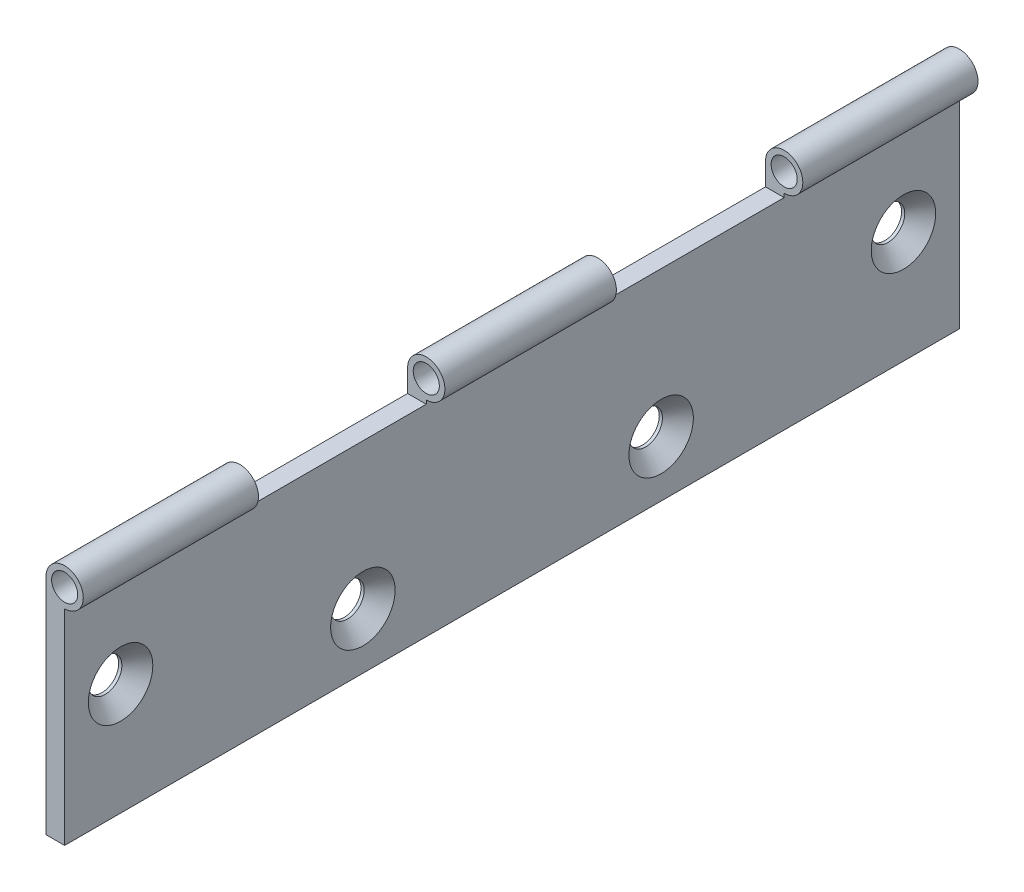
SolidWorks part; units mm, degrees
ref_plane "Front Plane" through (0, 0, 0) normal (0, 0, 1) x (1, 0, 0)
ref_plane "Top Plane" through (0, 0, 0) normal (0, 1, 0) x (1, 0, 0)
ref_plane "Right Plane" through (0, 0, 0) normal (1, 0, 0) x (0, 0, -1)
sketch "Эскиз1" plane through (0, 0, 0) normal (0, 0, 1) x (1, 0, 0)
  line L0 (0, 0) -> (0, 60)
  dimension "D1" = 60
extrude "Вытянуть-Тонкостенный1" add sketch "Эскиз1" along normal mid plane 240 thin
sketch "Эскиз2" plane through (0, 0, 120) normal (0, 0, 1) x (1, 0, 0)
  circle A0 centre (5, 60) radius 5
sweep "По траектории1" add profiles "Эскиз2" path edge at (5, 60, 0)
sketch "Эскиз4" plane through (0, 0, 120) normal (0, 0, 1) x (1, 0, 0)
  circle A0 centre (5, 60) radius 3.5
  arc A1 (5, 55) -> (0, 60) centre (5, 60) ccw construction
extrude "Вырез-Вытянуть1" cut sketch "Эскиз4" against normal through all
hole_wizard "Зенковка для  винта с плоской головкой M81" positions "Эскиз6" profile "Эскиз5" countersink size "M8" standard "Ansi Metric" end condition through all
sketch "Эскиз6" plane through (5, 0, 0) normal (1, 0, 0) x (0, 0, -1)
  point P0 (-105, 30)
  point P2 (-40, 15)
  dimension "D1" = 30
  dimension "D2" = 15
  dimension "D3" = 15
  dimension "D4" = 80
sketch "Эскиз5" plane through (5, 30, 105) normal (0, 1, 0) x (0, 0, -1)
  line L0 (0, 0) -> (0, 5)
  line L1 (0, 5) -> (4.5, 5)
  line L2 (4.5, 5) -> (4.5, 4.15)
  line L3 (4.5, 4.15) -> (8.65, 0)
  line L5 (8.65, 0) -> (0, 0)
  line L6 (-4.5, 4.15) -> (-8.65, 0) construction
  line L11 (0, -6.35) -> (0, 107.95) construction
  dimension "Диаметр сквозного отверстия" = 9
  dimension "Глубина сквозного отверстия" = 5
  dimension "Диаметр передней зенковки" = 17.3
  dimension "Угол передней зенковки" = 90
mirror "Зеркальное отражение1" about plane through (0, 0, 0) normal (0, 0, 1) of "Зенковка для  винта с плоской головкой M81"
sketch "компоновка для вырезов" plane through (5, 0, 0) normal (1, 0, 0) x (0, 0, -1)
  line L5 (-120, 65) -> (-120, 55) construction
  line L6 (120, 54) -> (-120, 54)
  line L7 (120, 54) -> (-120, 54)
  line L8 (120, 55) -> (120, 65) construction
  line L9 (-120, 65) -> (-120, 54)
  line L10 (120, 54) -> (120, 65)
  line L11 (-72, 65) -> (-72, 54)
  line L12 (-24, 65) -> (-24, 54)
  line L13 (120, 65) -> (-120, 65) construction
  line L14 (0, 96.9295) -> (0, 0) construction
  line L15 (24, 65) -> (24, 54)
  line L16 (72, 65) -> (72, 54)
  dimension "D2" = 48
  dimension "D3" = 48
  dimension "D1" = 1
sketch "Эскиз8" plane through (5, 0, 0) normal (1, 0, 0) x (0, 0, -1)
  line L1 (120, 54) -> (-120, 54) construction
  line L3 (-23, 54) -> (-73, 54)
  line L4 (73, 54) -> (23, 54)
  line L6 (73, 65) -> (23, 65)
  line L9 (-73, 65) -> (-73, 54)
  line L10 (-73, 65) -> (-73, 54)
  line L12 (-23, 65) -> (-23, 54)
  line L13 (-23, 65) -> (-23, 54)
  line L15 (73, 65) -> (73, 54)
  line L16 (73, 65) -> (73, 54)
  line L17 (-23, 65) -> (-73, 65)
  line L18 (23, 65) -> (23, 54)
  line L19 (23, 65) -> (23, 54)
  point P5 (-60, 65)
  dimension "D2" = 1
  dimension "D3" = 1
  dimension "D4" = 1
  dimension "D5" = 1
extrude "Вырез-Вытянуть2" cut sketch "Эскиз8" against normal through all both and the other way through all
equation "\"D1@Эскиз6\"= \"D1@Эскиз1\" / 2"
equation "\"D4@Эскиз6\"= \"D1@Вытянуть-Тонкостенный1\" / 3"
equation "\"D2@компоновка для вырезов\"= \"D1@Вытянуть-Тонкостенный1\" / 5"
equation "\"D3@компоновка для вырезов\"= \"D1@Вытянуть-Тонкостенный1\" / 5"
